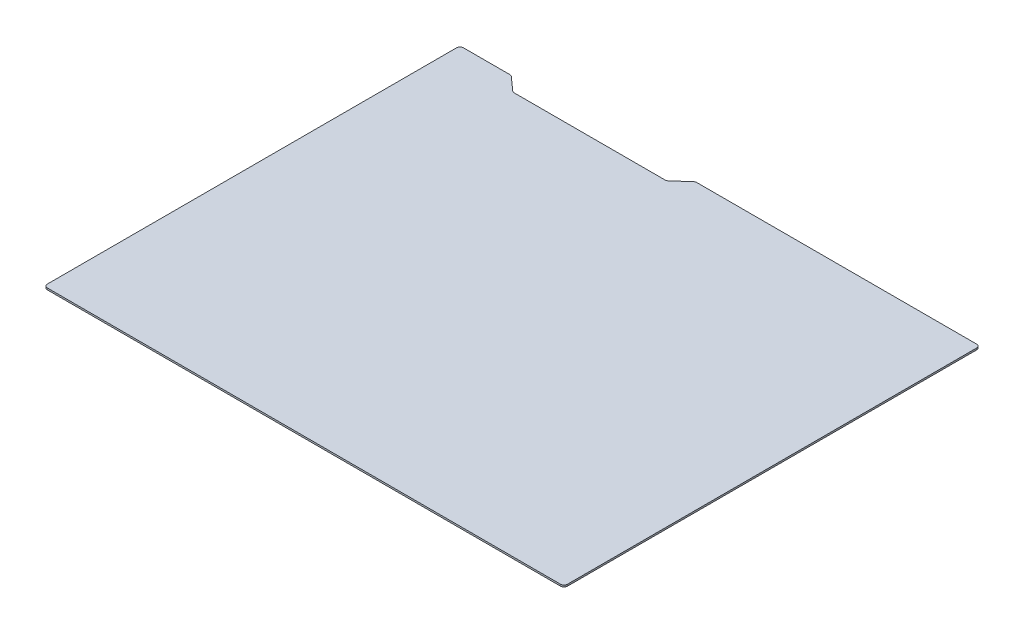
SolidWorks part; units mm, degrees
ref_plane "Front" through (0, 0, 0) normal (0, 0, 1) x (1, 0, 0)
ref_plane "Top" through (0, 0, 0) normal (0, 1, 0) x (1, 0, 0)
ref_plane "Right" through (0, 0, 0) normal (1, 0, 0) x (0, 0, -1)
sketch "Sketch1" plane through (0, 0, 0) normal (0, 1, 0) x (1, 0, 0)
  line L0 (-122.4, 121.92) -> (-122.4, 113.92) construction
  line L2 (-152.4, 121.92) -> (-152.4, -121.92)
  line L3 (-152.4, -121.92) -> (152.4, -121.92)
  line L4 (152.4, 121.92) -> (152.4, -121.92)
  line L5 (-152.4, 121.92) -> (152.4, -121.92) construction
  line L6 (-152.4, -121.92) -> (152.4, 121.92) construction
  line L7 (-122.4, 113.92) -> (-14.4, 113.92) construction
  line L8 (-14.4, 113.92) -> (-14.4, 121.92) construction
  line L9 (-152.4, 121.92) -> (-122.4, 121.92)
  line L10 (-14.4, 121.92) -> (152.4, 121.92)
  line L11 (-113.4, 113.92) -> (-23.4, 113.92)
  line L12 (-113.4, 113.92) -> (-122.4, 121.92)
  line L13 (-23.4, 113.92) -> (-14.4, 121.92)
  line L14 (-152.4, -103.4113) -> (152.4, -103.4113) construction
  line L15 (-152.4, -28.3759) -> (152.4, -28.3759) construction
  line L16 (-152.4, 117.1605) -> (152.4, 117.1605) construction
  line L17 (-144.732, -121.92) -> (-144.732, 121.92) construction
  line L18 (-54.0459, -121.92) -> (-54.0459, 117.1605) construction
  line L19 (137.139, -121.92) -> (137.139, 121.92) construction
  point P0 (0, 0)
  point P12 (-68.4, 113.92)
  point P13 (-68.4, 113.92)
  dimension "D1" = 304.8
  dimension "D2" = 243.84
  dimension "D3" = 30
  dimension "D4" = 108
  dimension "D5" = 90
  dimension "D6" = 8
extrude "Boss-Extrude1" add sketch "Sketch1" along normal blind 1
fillet "Fillet1" radius 2 4 edges at (-14.4, 0.5, -121.92) (-23.4, 0.5, -113.92) (-122.4, 0.5, -121.92) (-113.4, 0.5, -113.92)
fillet "Fillet2" radius 2 4 edges at (-152.4, 0.5, 121.92) (152.4, 0.5, 121.92) (152.4, 0.5, -121.92) (-152.4, 0.5, -121.92)
